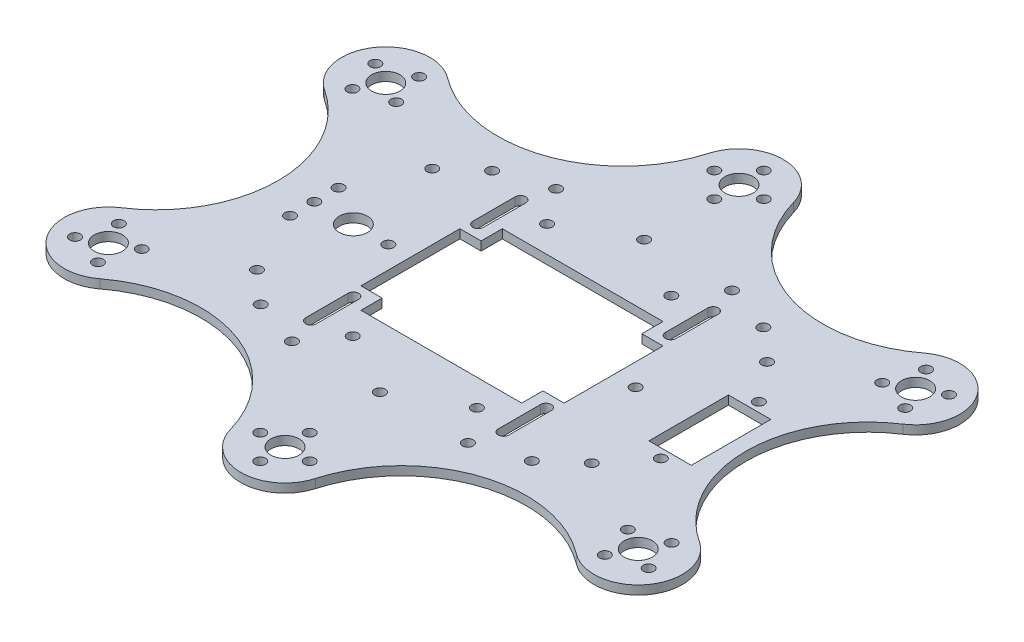
SolidWorks part; units mm, degrees
ref_plane "Front Plane" through (0, 0, 0) normal (0, 0, 1) x (1, 0, 0)
ref_plane "Top Plane" through (0, 0, 0) normal (0, 1, 0) x (1, 0, 0)
ref_plane "Right Plane" through (0, 0, 0) normal (1, 0, 0) x (0, 0, -1)
sketch "Sketch1" plane through (0, 0, 0) normal (0, 1, 0) x (1, 0, 0)
  line L0 (0, 79.6556) -> (0, -85.1852) construction
  line L2 (-28.75, -20) -> (-28.75, -17.65)
  line L4 (28.75, -20) -> (28.75, -17.65)
  line L5 (-28.75, -20) -> (28.75, 20) construction
  line L6 (-28.75, 20) -> (28.75, -20) construction
  line L7 (-91.2557, 0) -> (90.8672, 0) construction
  line L8 (0, 0) -> (74.9766, 39.25) construction
  line L9 (27.25, 17.65) -> (27.25, 29.65) construction
  line L10 (25.75, 17.65) -> (25.75, 29.65)
  line L11 (28.75, 17.65) -> (28.75, 29.65)
  line L12 (-22.75, 20) -> (-22.75, 14)
  line L14 (28.75, 20) -> (28.75, 17.65)
  line L15 (28.75, 14) -> (22.75, 14)
  line L16 (22.75, 20) -> (22.75, 14)
  line L17 (-28.75, 14) -> (-22.75, 14)
  line L18 (-28.75, 20) -> (-28.75, 17.65)
  line L20 (-27.25, 17.65) -> (-27.25, 29.65) construction
  line L21 (-25.75, 17.65) -> (-25.75, 29.65)
  line L22 (-28.75, 17.65) -> (-28.75, 29.65)
  line L24 (-28.75, -20) -> (-28.75, -17.65)
  line L25 (-28.75, -14) -> (-22.75, -14)
  line L26 (22.75, -20) -> (22.75, -14)
  line L27 (28.75, -14) -> (22.75, -14)
  line L28 (28.75, -20) -> (28.75, -17.65)
  line L30 (-22.75, -20) -> (-22.75, -14)
  line L31 (-74.9766, -39.25) -> (74.9766, 39.25) construction
  line L32 (-27.25, -17.65) -> (-27.25, -29.65) construction
  line L33 (-25.75, -17.65) -> (-25.75, -29.65)
  line L34 (-28.75, -17.65) -> (-28.75, -29.65)
  line L35 (27.25, -17.65) -> (27.25, -29.65) construction
  line L36 (25.75, -17.65) -> (25.75, -29.65)
  line L37 (28.75, -17.65) -> (28.75, -29.65)
  line L38 (66.25, 79.6556) -> (66.25, -85.1852) construction
  line L39 (-66.25, 79.6556) -> (-66.25, -85.1852) construction
  line L40 (-91.2557, 42) -> (90.8672, 42) construction
  line L41 (-91.2557, -42) -> (90.8672, -42) construction
  line L42 (-22.75, 20) -> (22.75, 20)
  line L43 (-28.75, 17.65) -> (-28.75, 20)
  line L44 (28.75, 17.65) -> (28.75, 20)
  line L45 (28.75, -14) -> (28.75, 14)
  line L46 (-22.75, -20) -> (22.75, -20)
  line L47 (-22.75, -20) -> (22.75, -20)
  line L48 (-28.75, -14) -> (-28.75, 14)
  line L49 (-74.9766, 39.25) -> (74.9766, -39.25) construction
  line L50 (0, 0) -> (-46.0262, -77.3558) construction
  line L52 (50, -11.25) -> (62, -11.25)
  line L53 (50, -11.25) -> (50, 11.25)
  line L54 (50, 11.25) -> (62, 11.25)
  line L55 (62, -11.25) -> (62, 11.25)
  line L56 (50, -11.25) -> (62, 11.25) construction
  line L57 (50, 11.25) -> (62, -11.25) construction
  circle A0 centre (0, 64.25) radius 4
  arc A1 (12.0221, 67.6732) -> (-12.0221, 67.6732) centre (0, 64.25) ccw
  circle A2 centre (0, 64.25) radius 7 construction
  circle A3 centre (-7, 64.25) radius 1.5
  circle A4 centre (0, 57.25) radius 1.5
  circle A5 centre (7, 64.25) radius 1.5
  circle A6 centre (0, 71.25) radius 1.5
  circle A7 centre (0, 37.375) radius 1.5
  circle A8 centre (17.575, 27.5) radius 1.5
  circle A9 centre (24.9, 37.375) radius 1.5
  circle A10 centre (38.375, 32.75) radius 1.5
  circle A11 centre (47.375, 24.8006) radius 1.5
  circle A12 centre (74.9766, 39.25) radius 4
  arc A13 (81.8194, 28.7893) -> (67.4147, 49.2033) centre (74.9766, 39.25) ccw
  circle A14 centre (74.9766, 39.25) radius 7 construction
  circle A15 centre (68.775, 36.0035) radius 1.5
  circle A16 centre (71.7301, 45.4516) radius 1.5
  circle A17 centre (81.1782, 42.4965) radius 1.5
  circle A18 centre (78.2231, 33.0484) radius 1.5
  arc A19 (25.75, 17.65) -> (28.75, 17.65) centre (27.25, 17.65) ccw
  arc A20 (28.75, 29.65) -> (25.75, 29.65) centre (27.25, 29.65) ccw
  circle A21 centre (35, 0) radius 1.5
  circle A22 centre (-35, 0) radius 1.5
  circle A23 centre (-47.375, 24.8006) radius 1.5
  circle A24 centre (-38.375, 32.75) radius 1.5
  circle A25 centre (-17.575, 27.5) radius 1.5
  arc A26 (-25.75, 17.65) -> (-28.75, 17.65) centre (-27.25, 17.65) cw
  arc A27 (-28.75, 29.65) -> (-25.75, 29.65) centre (-27.25, 29.65) cw
  circle A28 centre (-24.9, 37.375) radius 1.5
  circle A29 centre (-74.9766, 39.25) radius 7 construction
  circle A30 centre (-78.2231, 33.0484) radius 1.5
  circle A31 centre (-81.1782, 42.4965) radius 1.5
  circle A32 centre (-71.7301, 45.4516) radius 1.5
  circle A33 centre (-68.775, 36.0035) radius 1.5
  arc A34 (-81.8194, 28.7893) -> (-67.4147, 49.2033) centre (-74.9766, 39.25) cw
  circle A35 centre (-74.9766, 39.25) radius 4
  circle A36 centre (-24.9, -37.375) radius 1.5
  circle A37 centre (-17.575, -27.5) radius 1.5
  circle A38 centre (-38.375, -32.75) radius 1.5
  circle A39 centre (-47.375, -24.8006) radius 1.5
  circle A40 centre (47.375, -24.8006) radius 1.5
  circle A41 centre (38.375, -32.75) radius 1.5
  circle A42 centre (24.9, -37.375) radius 1.5
  circle A43 centre (17.575, -27.5) radius 1.5
  circle A44 centre (0, -37.375) radius 1.5
  arc A45 (-25.75, -17.65) -> (-28.75, -17.65) centre (-27.25, -17.65) ccw
  arc A46 (-28.75, -29.65) -> (-25.75, -29.65) centre (-27.25, -29.65) ccw
  arc A47 (25.75, -17.65) -> (28.75, -17.65) centre (27.25, -17.65) cw
  arc A48 (28.75, -29.65) -> (25.75, -29.65) centre (27.25, -29.65) cw
  circle A49 centre (0, -64.25) radius 7 construction
  circle A50 centre (0, -71.25) radius 1.5
  circle A51 centre (7, -64.25) radius 1.5
  circle A52 centre (0, -57.25) radius 1.5
  circle A53 centre (-7, -64.25) radius 1.5
  arc A54 (12.0221, -67.6732) -> (-12.0221, -67.6732) centre (0, -64.25) cw
  circle A55 centre (0, -64.25) radius 4
  circle A56 centre (74.9766, -39.25) radius 7 construction
  circle A57 centre (78.2231, -33.0484) radius 1.5
  circle A58 centre (81.1782, -42.4965) radius 1.5
  circle A59 centre (71.7301, -45.4516) radius 1.5
  circle A60 centre (68.775, -36.0035) radius 1.5
  arc A61 (81.8194, -28.7893) -> (67.4147, -49.2033) centre (74.9766, -39.25) cw
  circle A62 centre (74.9766, -39.25) radius 4
  circle A63 centre (-74.9766, -39.25) radius 7 construction
  circle A64 centre (-74.9766, -39.25) radius 4
  arc A65 (-81.8194, -28.7893) -> (-67.4147, -49.2033) centre (-74.9766, -39.25) ccw
  circle A66 centre (-68.775, -36.0035) radius 1.5
  circle A67 centre (-71.7301, -45.4516) radius 1.5
  circle A68 centre (-81.1782, -42.4965) radius 1.5
  circle A69 centre (-78.2231, -33.0484) radius 1.5
  arc A70 (-81.8194, -28.7893) -> (-81.8194, 28.7893) centre (-100.6518, 0) ccw
  arc A71 (81.8194, -28.7893) -> (81.8194, 28.7893) centre (100.6518, 0) cw
  arc A72 (-12.0221, -67.6732) -> (-67.4147, -49.2033) centre (-46.0262, -77.3558) ccw
  arc A73 (-12.0221, 67.6732) -> (-67.4147, 49.2033) centre (-46.0262, 77.3558) cw
  arc A74 (12.0221, -67.6732) -> (67.4147, -49.2033) centre (46.0262, -77.3558) cw
  arc A75 (12.0221, 67.6732) -> (67.4147, 49.2033) centre (46.0262, 77.3558) ccw
  circle A76 centre (56, 13.875) radius 1.5
  circle A77 centre (56, -13.875) radius 1.5
  circle A78 centre (-44.9, 0) radius 4
  circle A79 centre (-55.95, 0) radius 1.5
  circle A80 centre (-55.95, 6.875) radius 1.5
  circle A81 centre (-55.95, -6.875) radius 1.5
  point P0 (0, 0)
  point P25 (0, 64.25)
  point P42 (27.25, 23.65)
  point P49 (74.9766, 39.25)
  point P72 (-27.25, 23.65)
  point P89 (56, 0)
  point P91 (-74.9766, 39.25)
  point P121 (-27.25, -23.65)
  point P128 (27.25, -23.65)
  point P145 (0, -64.25)
  point P158 (74.9766, -39.25)
  point P171 (-74.9766, -39.25)
  point P210 (0, 0)
  point P211 (0, 0)
  dimension "D3" = 25
  dimension "D4" = 8
  dimension "D5" = 14
  dimension "D6" = 3
  dimension "D11" = 3.65
  dimension "D1" = 40
  dimension "D2" = 57.5
  dimension "D9" = 12
  dimension "D10" = 3
  dimension "D12" = 40
  dimension "D13" = 74.75
  dimension "D14" = 24.9
  dimension "D15" = 137.55
  dimension "D16" = 28
  dimension "D17" = 35.15
  dimension "D18" = 70
  dimension "D19" = 94.75
  dimension "D20" = 78.5
  dimension "D21" = 76.75
  dimension "D22" = 65.5
  dimension "D23" = 128.5
  dimension "D24" = 132.5
  dimension "D25" = 84
  dimension "D26" = 55
  dimension "D27" = 12
  dimension "D28" = 22.5
  dimension "D29" = 21.25
  dimension "D30" = 27.75
  dimension "D31" = 13.75
  dimension "D32" = 11.05
  dimension "D33" = 9.9
  dimension "D34" = 27.632
  dimension "D35" = 39.25
  dimension "D36" = 74.9766
  dimension "D37" = 64.25
  dimension "D7" = 4
  dimension "D8" = 4
extrude "Boss-Extrude1" add sketch "Sketch1" along normal blind 2.5 contours A75 A1 A73 A34 A70 A65 A72 A54 A74 A61 A71 A13 A77 A76 A69 A68 A67 A66 A64 A60 A58 A55 A52 A50 A46 L34 L2 A45 L33 A43 A41 A35 A32
